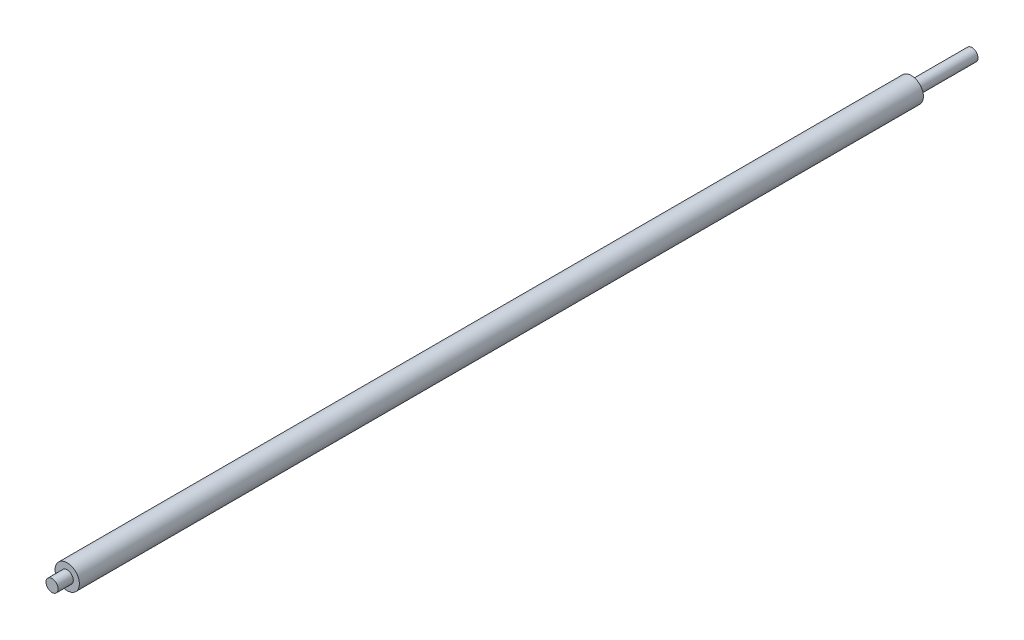
SolidWorks part; units mm, degrees
ref_plane "Front Plane" through (0, 0, 0) normal (0, 0, 1) x (1, 0, 0)
ref_plane "Top Plane" through (0, 0, 0) normal (0, 1, 0) x (1, 0, 0)
ref_plane "Right Plane" through (0, 0, 0) normal (1, 0, 0) x (0, 0, -1)
sketch "Sketch1" plane through (0, 0, 0) normal (0, 0, 1) x (1, 0, 0)
  circle A0 centre (0, 0) radius 6
  dimension "D1" = 12
extrude "Boss-Extrude1" add sketch "Sketch1" along normal mid plane 417.5
sketch "Sketch2" plane through (0, 0, 208.75) normal (0, 0, 1) x (1, 0, 0)
  circle A1 centre (0, 0) radius 3
  dimension "D2" = 6
sketch "Sketch3" plane through (0, 0, -208.75) normal (0, 0, -1) x (-1, 0, 0)
  circle A1 centre (0, 0) radius 3
  dimension "D1" = 6
extrude "Boss-Extrude4" add sketch "Sketch2" along normal blind 7.5
extrude "Boss-Extrude5" add sketch "Sketch3" along normal blind 30
